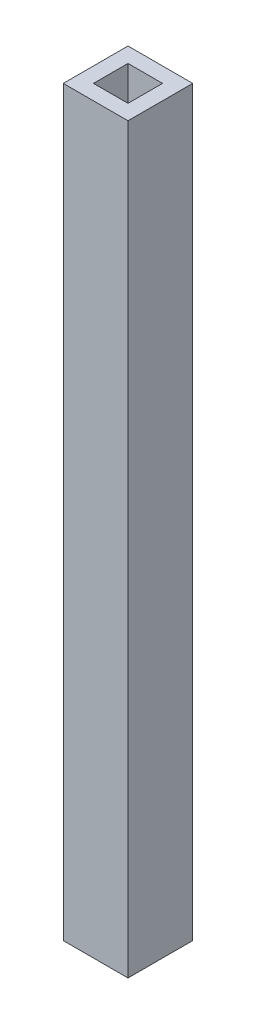
SolidWorks part; units mm, degrees
ref_plane "Front Plane" through (0, 0, 0) normal (0, 0, 1) x (1, 0, 0)
ref_plane "Top Plane" through (0, 0, 0) normal (0, 1, 0) x (1, 0, 0)
ref_plane "Right Plane" through (0, 0, 0) normal (1, 0, 0) x (0, 0, -1)
sketch "Sketch1" plane through (0, 0, 0) normal (0, 1, 0) x (1, 0, 0)
  line L1 (-75, 75) -> (75, 75)
  line L2 (-75, 75) -> (-75, -75)
  line L3 (-75, -75) -> (75, -75)
  line L4 (75, 75) -> (75, -75)
  line L5 (-75, 75) -> (75, -75) construction
  line L6 (-75, -75) -> (75, 75) construction
  line L7 (-40, 40) -> (40, 40)
  line L8 (-40, 40) -> (-40, -40)
  line L9 (-40, -40) -> (40, -40)
  line L10 (40, 40) -> (40, -40)
  line L11 (-40, 40) -> (40, -40) construction
  line L12 (-40, -40) -> (40, 40) construction
  point P0 (0, 0)
  point P6 (0, 0)
  dimension "D1" = 150
  dimension "D2" = 150
  dimension "D3" = 80
extrude "Boss-Extrude1" add sketch "Sketch1" along normal blind 1720
